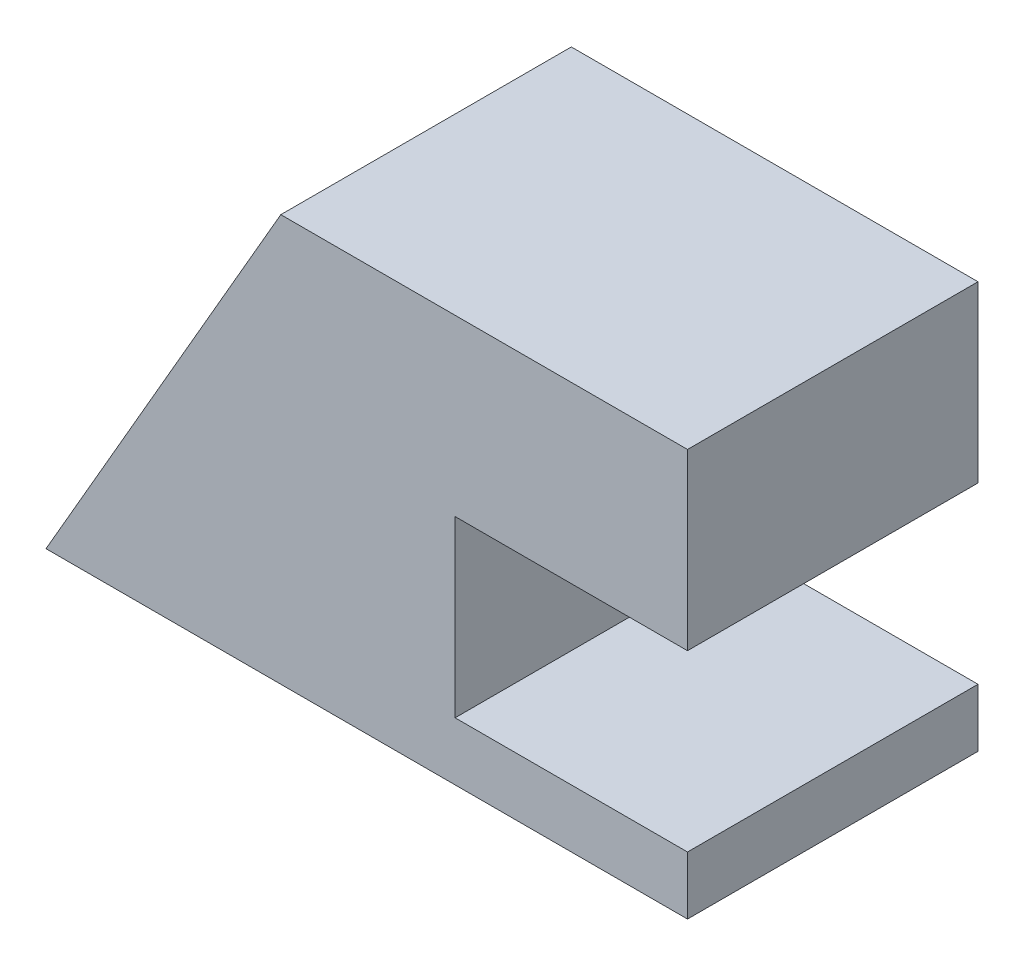
SolidWorks part; units mm, degrees
ref_plane "Front Plane" through (0, 0, 0) normal (0, 0, 1) x (1, 0, 0)
ref_plane "Top Plane" through (0, 0, 0) normal (0, 1, 0) x (1, 0, 0)
ref_plane "Right Plane" through (0, 0, 0) normal (1, 0, 0) x (0, 0, -1)
sketch "Sketch1" plane through (0, 0, 0) normal (0, 0, 1) x (1, 0, 0)
  line L0 (11.0415, 7) -> (4.0415, 7)
  line L1 (4.0415, 7) -> (0, 0)
  line L2 (0, 0) -> (11.0415, 0)
  line L3 (11.0415, 0) -> (11.0415, 1)
  line L4 (11.0415, 1) -> (7.0415, 1)
  line L5 (7.0415, 1) -> (7.0415, 4)
  line L6 (7.0415, 4) -> (11.0415, 4)
  line L7 (11.0415, 4) -> (11.0415, 7)
  point P7 (-34.4732, 2.8684)
  point P9 (0, 0)
  point P11 (11.0415, 7)
  dimension "D1" = 60
  dimension "D2" = 3
  dimension "D3" = 3
  dimension "D4" = 1
  dimension "D5" = 4
  dimension "D6" = 3
extrude "Boss-Extrude1" add sketch "Sketch1" along normal blind 5
